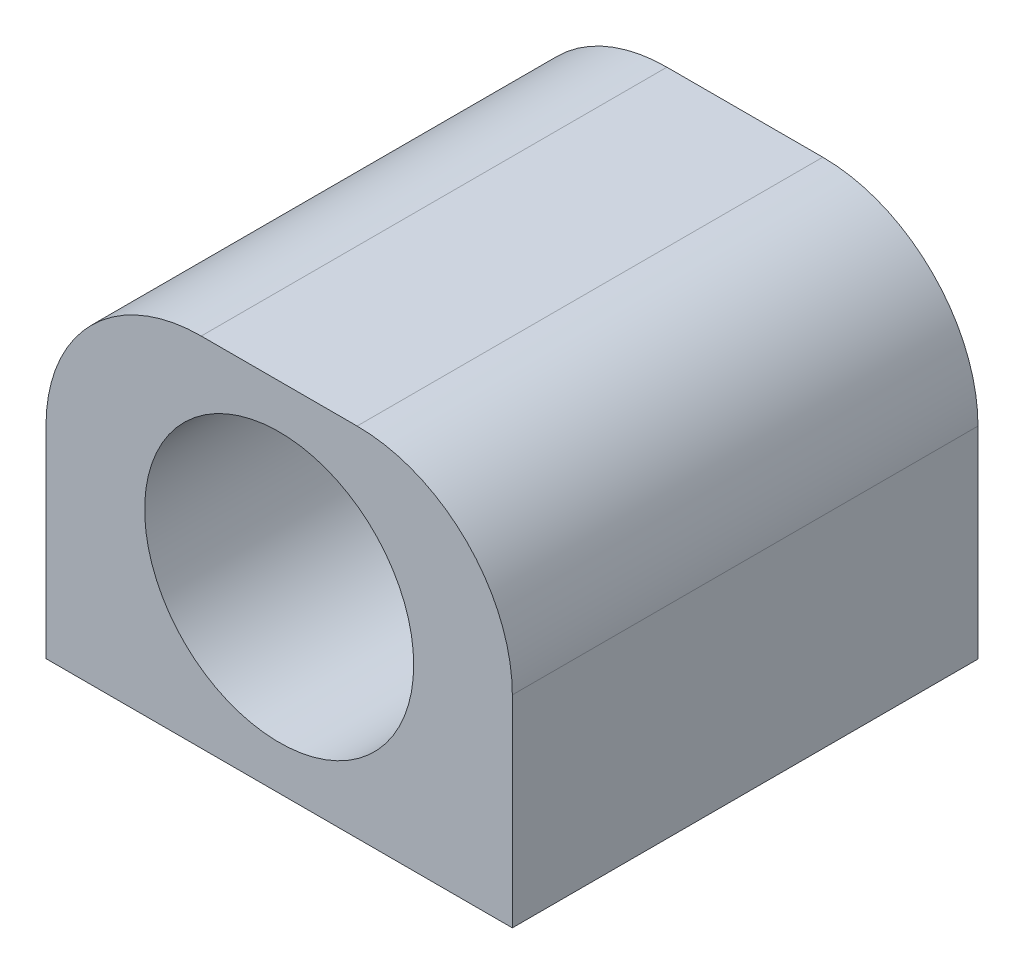
SolidWorks part; units mm, degrees
ref_plane "前视基准面" through (0, 0, 0) normal (0, 0, 1) x (1, 0, 0)
ref_plane "上视基准面" through (0, 0, 0) normal (0, 1, 0) x (1, 0, 0)
ref_plane "右视基准面" through (0, 0, 0) normal (1, 0, 0) x (0, 0, -1)
sketch "草图1" plane through (0, 0, 0) normal (0, 0, 1) x (1, 0, 0)
  line L0 (112.5, 0) -> (-27.5, 0) construction
  line L1 (47.5218, 23) -> (37.4782, 23)
  line L2 (57.5218, 13) -> (57.5218, 0)
  line L3 (57.5218, 0) -> (27.4782, 0)
  line L4 (27.4782, 13) -> (27.4782, 0)
  line L5 (57.5218, 23) -> (27.4782, 0) construction
  line L6 (57.5218, 0) -> (27.4782, 23) construction
  circle A0 centre (42.5, 11.5) radius 8.6667 construction
  circle A1 centre (42.5, 11.5) radius 8.6667
  arc A2 (47.5218, 23) -> (57.5218, 13) centre (47.5218, 13) cw
  arc A3 (37.4782, 23) -> (27.4782, 13) centre (37.4782, 13) ccw
  dimension "D1" = 10
extrude "凸台-拉伸1" add sketch "草图1" against normal blind 30 from offset 30
